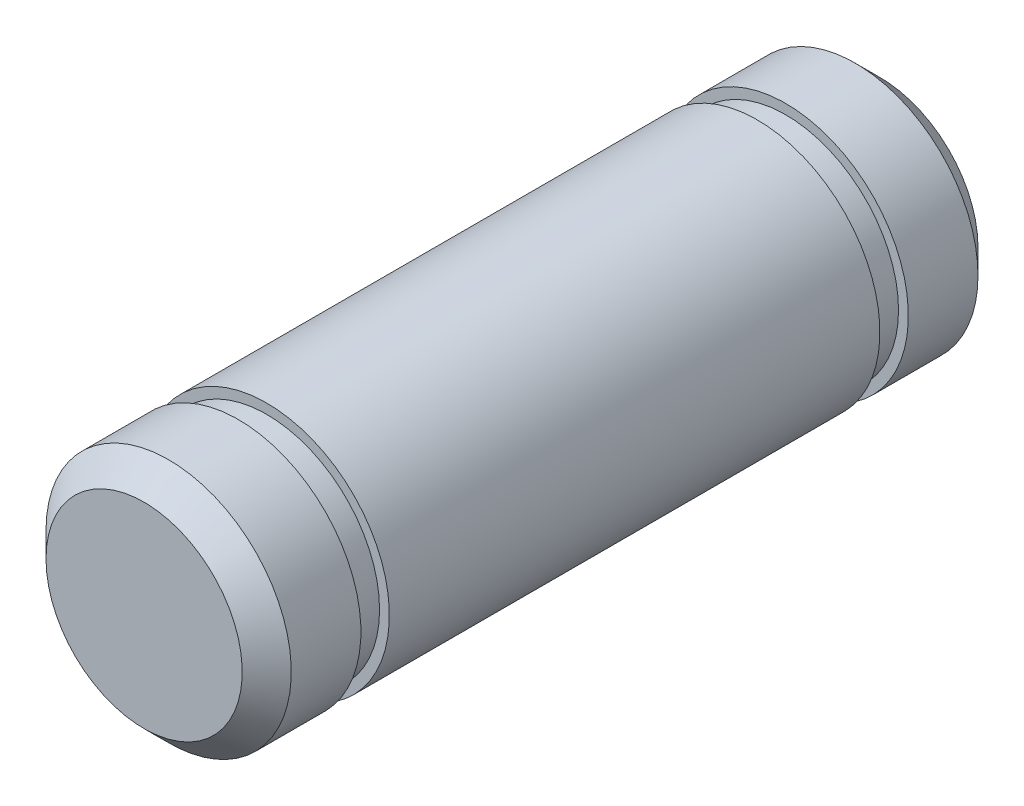
SolidWorks part; units mm, degrees
ref_plane "Front" through (0, 0, 0) normal (0, 0, 1) x (1, 0, 0)
ref_plane "Top" through (0, 0, 0) normal (0, 1, 0) x (1, 0, 0)
ref_plane "Right" through (0, 0, 0) normal (1, 0, 0) x (0, 0, -1)
sketch "Sketch1" plane through (0, 0, 0) normal (0, 0, 1) x (1, 0, 0)
  circle A0 centre (0, 0) radius 3.175
  dimension "dia" = 6.35
sketch "Sketch2" plane through (0, 0, 0) normal (1, 0, 0) x (0, 0, -1)
  line L0 (-76.2, 0) -> (76.2, 0) construction
  line L1 (5.2388, 0) -> (-5.2388, 0) construction
  line L3 (76.2, 3.175) -> (76.2, -3.175) construction
  line L4 (-76.2, 3.175) -> (-76.2, -3.175) construction
  line L5 (-57.15, 3.175) -> (-57.15, -3.175) construction
  line L6 (57.15, 3.175) -> (57.15, -3.175) construction
  point P6 (0, 0)
  point P10 (76.2, 0)
  point P13 (-76.2, 0)
  point P16 (-57.15, 0)
  point P19 (57.15, 0)
  dimension "D1" = 6.35
  dimension "lg" = 152.4
  dimension "D2" = 19.05
  dimension "D3" = 19.05
sketch "Sketch3" plane through (0, 0, 0) normal (0, 0, 1) x (1, 0, 0)
  line L0 (0, 3.175) -> (0, -3.175) construction
  circle A0 centre (0, 0) radius 3.175
  dimension "D1" = 6.35
extrude "Boss-Extrude1" add sketch "Sketch3" along normal mid plane 152.4
chamfer "Chamfer1" distance 0.635 angle 45 2 edges at (3.175, 0, -76.2) (3.175, 0, 76.2)
sketch "Sketch4" plane through (0, 0, -76.2) normal (0, 0, -1) x (-1, 0, 0)
  circle A0 centre (0, 0) radius 3.175
  circle A1 centre (0, 0) radius 3.175 construction
extrude "CUT-TO-LENGTH" cut sketch "Sketch4" against normal through all from offset 19.05 offset against normal yes
chamfer "CHAMER-CUT-END" distance 0.635 angle 45 1 edges at (-3.175, 0, -57.15)
ref_axis "Axis1" through (0, 0, -57.785) along (0, 0, -1)
sketch "Sketch5" plane through (0, 0, 0) normal (0, 1, 0) x (1, 0, 0)
  line L0 (3.175, 57.785) -> (3.175, 75.565) construction
  line L1 (3.175, 60.325) -> (2.921, 60.325)
  line L2 (3.175, 60.325) -> (3.175, 59.5884)
  line L3 (3.175, 59.5884) -> (2.921, 59.5884)
  line L4 (2.921, 60.325) -> (2.921, 59.5884)
  line L5 (3.175, 60.325) -> (2.921, 59.5884) construction
  line L6 (3.175, 59.5884) -> (2.921, 60.325) construction
  line L7 (2.921, 76.2) -> (2.921, 73.7616) construction
  line L8 (3.175, 73.7616) -> (2.921, 73.7616)
  line L9 (3.175, 73.7616) -> (3.175, 73.025)
  line L10 (3.175, 73.025) -> (2.921, 73.025)
  line L11 (2.921, 73.7616) -> (2.921, 73.025)
  line L12 (3.175, 73.7616) -> (2.921, 73.025) construction
  line L13 (3.175, 73.025) -> (2.921, 73.7616) construction
  line L14 (2.54, 76.2) -> (-2.54, 76.2) construction
  line L15 (2.921, 59.5884) -> (2.921, 57.15) construction
  line L16 (-2.54, 57.15) -> (2.54, 57.15) construction
  point P4 (3.048, 59.9567)
  point P11 (3.048, 73.3933)
  point P12 (0.9452, 69.9001)
  point P19 (0.7127, 73.2396)
  point P20 (3.175, 73.6498)
  point P23 (2.921, 61.0019)
  point P24 (2.8272, 72.1973)
  dimension "D1" = 0.7366
  dimension "D2" = 0.254
  dimension "D3" = 12.7
revolve "SNAP-RING-CUT" cut sketch "Sketch5" angle 360 about axis through (0, 0, -57.785) along (0, 0, -1)
equation "\"D1@Sketch2\" = \"dia@Sketch1\""
equation "\"D1@Sketch3\"=\"dia@Sketch1\""
equation "\"D1@Boss-Extrude1\"=\"lg@Sketch2\""
equation "\"D1@Chamfer1\"=\"dia@Sketch1\"*.1"
equation "\"D1@CHAMER-CUT-END\"=\"dia@Sketch1\"*.1"
equation "\"groove_width\"= 0.029"
equation "\"groove_depth\"= 0.01"
equation "\"D1@Sketch5\"=\"groove_width\""
equation "\"D2@Sketch5\"=\"groove_depth\""
